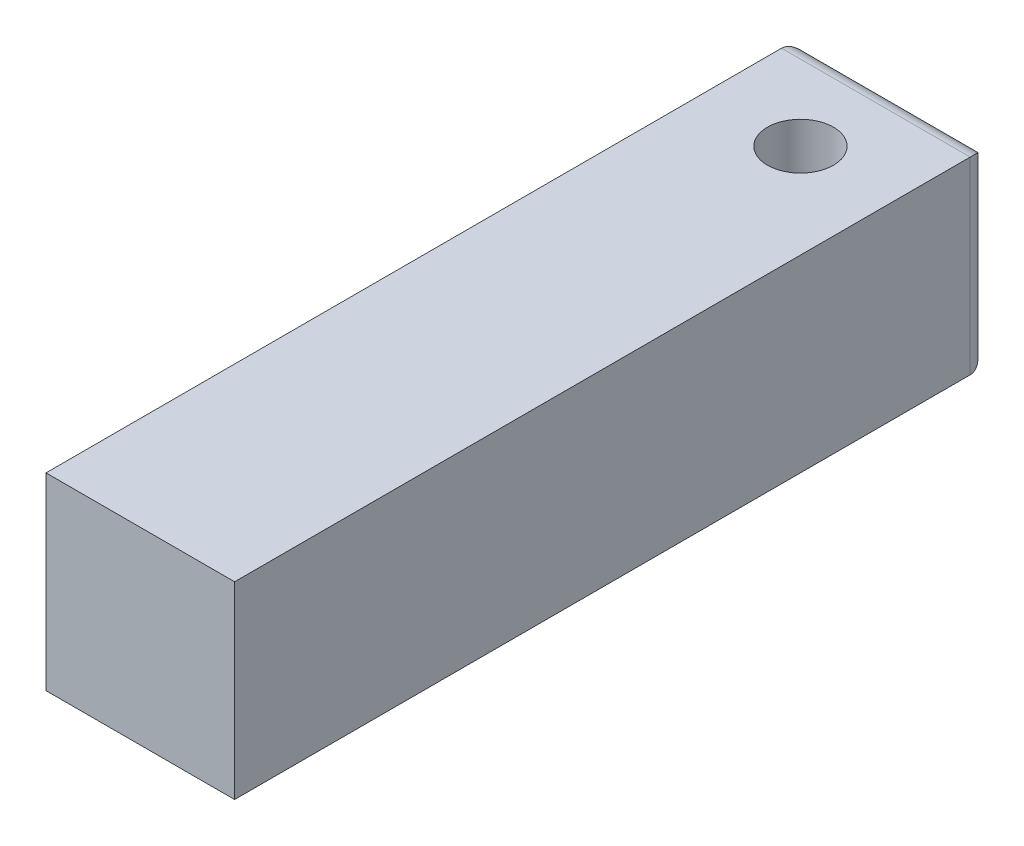
SolidWorks part; units mm, degrees
ref_plane "Ebene vorne" through (0, 0, 0) normal (0, 0, 1) x (1, 0, 0)
ref_plane "Ebene oben" through (0, 0, 0) normal (0, 1, 0) x (1, 0, 0)
ref_plane "Ebene rechts" through (0, 0, 0) normal (1, 0, 0) x (0, 0, -1)
sketch "Skizze1" plane through (0, 0, 0) normal (0, 1, 0) x (1, 0, 0)
  line L1 (0, 0) -> (-10, 0)
  line L2 (0, 0) -> (0, 40)
  line L3 (0, 40) -> (-10, 40)
  line L4 (-10, 0) -> (-10, 40)
  circle A0 centre (-5, 35) radius 1.75
  dimension "D4" = 3.5
  dimension "D1" = 10
  dimension "D2" = 40
  dimension "D3" = 5
  dimension "D5" = 5
extrude "Aufsatz-Linear austragen1" add sketch "Skizze1" against normal blind 10
fillet "Verrundung1" radius 1 4 edges at (-5, 0, -40) (-5, -10, -40) (-10, -5, -40) (0, -5, -40)
